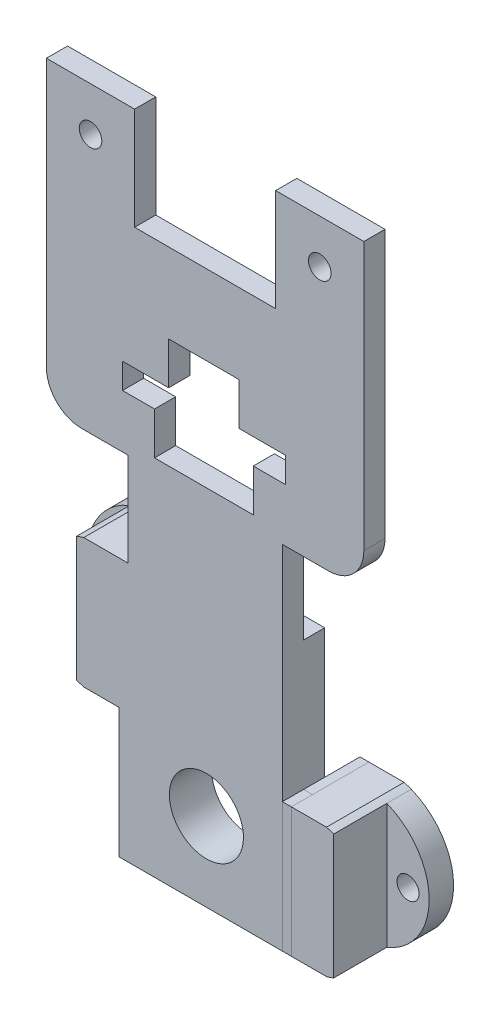
SolidWorks part; units mm, degrees
ref_plane "Front Plane" through (0, 0, 0) normal (0, 0, 1) x (1, 0, 0)
ref_plane "Top Plane" through (0, 0, 0) normal (0, 1, 0) x (1, 0, 0)
ref_plane "Right Plane" through (0, 0, 0) normal (1, 0, 0) x (0, 0, -1)
sketch "Sketch1" plane through (0, 0, 1119.4837) normal (0, 0, -1) x (-1, 0, 0)
  line L0 (-1148.8299, 505.6656) -> (-1128.8299, 505.6656) construction
  line L2 (-1161.3299, 505.6656) -> (-1161.3299, 518.1656)
  line L3 (-1161.3299, 518.1656) -> (-1148.8299, 518.1656)
  line L4 (-1148.8299, 505.6656) -> (-1148.8299, 518.1656)
  line L5 (-1161.3299, 505.6656) -> (-1148.8299, 518.1656) construction
  line L6 (-1161.3299, 518.1656) -> (-1148.8299, 505.6656) construction
  line L8 (-1128.8299, 505.6656) -> (-1128.8299, 518.1656)
  line L9 (-1128.8299, 518.1656) -> (-1116.3299, 518.1656)
  line L10 (-1116.3299, 505.6656) -> (-1116.3299, 518.1656)
  line L11 (-1128.8299, 505.6656) -> (-1116.3299, 518.1656) construction
  line L12 (-1128.8299, 518.1656) -> (-1116.3299, 505.6656) construction
  line L13 (-1128.8299, 505.6656) -> (-1148.8299, 505.6656) construction
  line L14 (-1148.8299, 518.1656) -> (-1128.8299, 518.1656) construction
  line L15 (-1138.8299, 518.1656) -> (-1138.8299, 426.1802) construction
  line L16 (-1148.8299, 505.6656) -> (-1128.8299, 505.6656) construction
  arc A0 (-1161.3299, 505.6656) -> (-1116.3299, 505.6656) centre (-1138.8299, 530.6919) ccw
  spline S0 degree 3 poles (-1148.8299, 505.6656) (-1142.1633, 505.6656) (-1135.4966, 505.6656) (-1128.8299, 505.6656) knots 0.277778 0.277778 0.277778 0.277778 0.722222 0.722222 0.722222 0.722222
  point P4 (-1155.0799, 511.9156)
  point P11 (-1122.5799, 511.9156)
  dimension "D1" = 33.6536
  dimension "D2" = 45
extrude "Boss-Extrude1" add sketch "Sketch1" along normal up to surface (17.8062 mm away)
sketch "Sketch4" plane through (0, 0, 1101.6775) normal (0, 0, -1) x (-1, 0, 0)
  line L0 (-1149.7799, 462.2666) -> (-1127.8799, 462.2666) construction
  line L1 (-1149.7799, 462.2666) -> (-1149.7799, 489.3928)
  line L2 (-1127.8799, 462.2666) -> (-1127.8799, 489.3928)
  line L4 (-1116.3299, 518.1656) -> (-1116.3299, 505.6656) construction
  line L5 (-1161.3299, 499.3928) -> (-1159.7799, 499.3928)
  line L6 (-1161.3299, 499.3928) -> (-1161.3299, 511.9156)
  line L7 (-1161.3299, 511.9156) -> (-1116.3299, 511.9156)
  line L8 (-1116.3299, 499.3928) -> (-1116.3299, 511.9156)
  line L9 (-1161.3299, 499.3928) -> (-1116.3299, 511.9156) construction
  line L10 (-1161.3299, 511.9156) -> (-1116.3299, 499.3928) construction
  line L11 (-1138.8299, 511.9156) -> (-1138.8299, 398.1731) construction
  line L12 (-1117.8799, 499.3928) -> (-1116.3299, 499.3928)
  line L13 (-1149.7799, 462.2666) -> (-1127.8799, 462.2666)
  arc A0 (-1127.5799, 461.9666) -> (-1127.8799, 462.2666) centre (-1127.8799, 461.9666) ccw construction
  arc A1 (-1127.5799, 461.9666) -> (-1127.8799, 462.2666) centre (-1127.8799, 461.9666) ccw construction
  arc A2 (-1117.8799, 499.3928) -> (-1127.8799, 489.3928) centre (-1117.8799, 489.3928) ccw
  arc A3 (-1149.7799, 489.3928) -> (-1159.7799, 499.3928) centre (-1159.7799, 489.3928) ccw
  point P11 (-1138.8299, 505.6542)
  point P22 (-1127.8799, 499.3928)
  dimension "D3" = 10
  dimension "D1" = 22.5
  dimension "D2" = 12.5228
extrude "Boss-Extrude2" add sketch "Sketch4" along normal blind 3
sketch "Sketch5" plane through (0, 462.2666, 0) normal (0, -1, 0) x (1, 0, 0)
  line L1 (1127.8799, 1098.6775) -> (1149.7799, 1098.6775)
  line L2 (1127.8799, 1098.6775) -> (1127.8799, 1101.6775)
  line L3 (1127.8799, 1101.6775) -> (1149.7799, 1101.6775)
  line L4 (1149.7799, 1098.6775) -> (1149.7799, 1101.6775)
  line L5 (1127.8799, 1098.6775) -> (1149.7799, 1101.6775) construction
  line L6 (1127.8799, 1101.6775) -> (1149.7799, 1098.6775) construction
  point P4 (1138.8299, 1100.1775)
extrude "Boss-Extrude3" add sketch "Sketch5" along normal up to surface (37 mm away)
sketch "Sketch7" plane through (0, 0, 1098.6775) normal (0, 0, -1) x (-1, 0, 0)
  circle A0 centre (-1139.0099, 436.4591) radius 5.25
  dimension "D1" = 10.5
extrude "Cut-Extrude1" cut sketch "Sketch7" against normal up to next
sketch "Sketch8" plane through (1127.8799, 0, 0) normal (-1, 0, 0) x (0, 0, 1)
  line L0 (1101.6775, 425.2666) -> (1101.6775, 489.3928) construction
  line L1 (1098.6775, 425.2666) -> (1101.6775, 425.2666)
  line L2 (1098.6775, 425.2666) -> (1098.6775, 461.9666)
  line L3 (1098.6775, 461.9666) -> (1101.6775, 461.9666)
  line L4 (1101.6775, 425.2666) -> (1101.6775, 461.9666)
  line L5 (1098.6775, 425.2666) -> (1101.6775, 461.9666) construction
  line L6 (1098.6775, 461.9666) -> (1101.6775, 425.2666) construction
  line L7 (1101.6775, 461.9666) -> (1101.9775, 461.9666) construction
  point P4 (1100.1775, 443.6166)
extrude "Boss-Extrude4" add sketch "Sketch8" along normal blind 1.27 separate body
sketch "Sketch9" plane through (1126.6099, 0, 0) normal (-1, 0, 0) x (0, 0, 1)
  line L0 (1101.6775, 425.2666) -> (1101.6775, 461.9666) construction
  line L1 (1098.6775, 461.9666) -> (1101.6775, 461.9666)
  line L2 (1098.6775, 461.9666) -> (1098.6775, 443.6166)
  line L3 (1098.6775, 443.6166) -> (1101.6775, 443.6166)
  line L4 (1101.6775, 461.9666) -> (1101.6775, 443.6166)
  line L5 (1098.6775, 461.9666) -> (1101.6775, 443.6166) construction
  line L6 (1098.6775, 443.6166) -> (1101.6775, 461.9666) construction
  point P4 (1100.1775, 452.7916)
extrude "Boss-Extrude5" add sketch "Sketch9" along normal blind 6
sketch "Sketch11" plane through (0, 0, 1101.6775) normal (0, 0, 1) x (1, 0, 0)
  line L1 (1120.6099, 461.9666) -> (1126.6099, 461.9666)
  line L2 (1120.6099, 461.9666) -> (1120.6099, 443.6166)
  line L3 (1120.6099, 443.6166) -> (1126.6099, 443.6166)
  line L4 (1126.6099, 461.9666) -> (1126.6099, 443.6166)
  line L5 (1120.6099, 461.9666) -> (1126.6099, 443.6166) construction
  line L6 (1120.6099, 443.6166) -> (1126.6099, 461.9666) construction
  point P4 (1123.6099, 452.7916)
extrude "Boss-Extrude6" add sketch "Sketch11" along normal blind 8
sketch "Sketch12" plane through (1120.6099, 0, 0) normal (-1, 0, 0) x (0, 0, 1)
  line L0 (1109.9156, 461.9666) -> (1101.9775, 461.9666) construction
  line L1 (1109.6775, 443.6166) -> (1103.6775, 443.6166)
  line L2 (1109.6775, 443.6166) -> (1109.6775, 461.9666)
  line L3 (1109.6775, 461.9666) -> (1103.6775, 461.9666)
  line L4 (1103.6775, 443.6166) -> (1103.6775, 461.9666)
  line L5 (1109.6775, 443.6166) -> (1103.6775, 461.9666) construction
  line L6 (1109.6775, 461.9666) -> (1103.6775, 443.6166) construction
  point P4 (1106.6775, 452.7916)
  dimension "D1" = 6
extrude "Boss-Extrude7" add sketch "Sketch12" along normal blind 6
sketch "Sketch14" plane through (0, 0, 1103.6775) normal (0, 0, -1) x (-1, 0, 0)
  line L0 (-1114.6099, 452.7916) -> (-1120.6099, 452.7916) construction
  line L1 (-1114.6099, 461.9666) -> (-1114.6099, 443.6166) construction
  line L2 (-1120.6099, 461.9666) -> (-1120.6099, 443.6166) construction
  circle A0 centre (-1117.6099, 452.7916) radius 1.5625
  dimension "D1" = 3.125
extrude "Cut-Extrude2" cut sketch "Sketch14" against normal through all
sketch "Sketch16" plane through (0, 0, 1098.6775) normal (0, 0, -1) x (-1, 0, 0)
  line L0 (-1126.6099, 443.6166) -> (-1126.6099, 461.9666) construction
  line L1 (-1120.6099, 461.9666) -> (-1127.8799, 461.9666) construction
  line L2 (-1126.6099, 461.9666) -> (-1126.6099, 463.8787)
  line L3 (-1126.6099, 463.8787) -> (-1111.6099, 463.8787)
  line L4 (-1111.6099, 463.8787) -> (-1111.6099, 441.8787)
  line L5 (-1111.6099, 441.8787) -> (-1126.6099, 441.8787)
  line L6 (-1126.6099, 443.6166) -> (-1126.6099, 425.2666) construction
  line L7 (-1126.6099, 441.8787) -> (-1126.6099, 443.6166)
  arc A0 (-1126.6099, 461.9666) -> (-1126.6099, 443.6166) centre (-1124.1175, 452.7916) cw
  dimension "D1" = 9.5075
  dimension "D2" = 15
  dimension "D3" = 22
  dimension "D4" = 1.9121
extrude "Cut-Extrude3" cut sketch "Sketch16" against normal through all
sketch "Sketch17" plane through (0, 0, 1098.6775) normal (0, 0, -1) x (-1, 0, 0)
  circle A0 centre (-1122.5799, 511.9156) radius 1.6
  circle A1 centre (-1155.0799, 511.9156) radius 1.6
  dimension "D1" = 3.2
extrude "Cut-Extrude4" cut sketch "Sketch17" against normal through all
sketch "Sketch18" plane through (0, 0, 1098.6775) normal (0, 0, -1) x (-1, 0, 0)
  circle A0 centre (-1155.0799, 511.9156) radius 2.5
  circle A1 centre (-1122.5799, 511.9156) radius 2.5
  dimension "D1" = 5
extrude "Cut-Extrude5" cut sketch "Sketch18" against normal up to surface (3 mm away) up to face at (1155.0799, 514.2656, 1101.6775)
fillet "Fillet8" radius 2 1 edges
ref_plane "Plane1" through (1138.8299, 0, 0) normal (1, 0, 0) x (0, 0, -1)
sketch "Sketch19" plane through (1149.7799, 0, 0) normal (1, 0, 0) x (0, 0, -1)
  line L0 (-1098.6775, 489.3928) -> (-1098.6775, 425.2666) construction
  line L1 (-1101.6775, 425.2666) -> (-1098.6775, 425.2666)
  line L2 (-1101.6775, 425.2666) -> (-1101.6775, 443.6166)
  line L3 (-1101.6775, 443.6166) -> (-1098.6775, 443.6166)
  line L4 (-1098.6775, 425.2666) -> (-1098.6775, 443.6166)
  line L5 (-1101.6775, 425.2666) -> (-1098.6775, 443.6166) construction
  line L6 (-1101.6775, 443.6166) -> (-1098.6775, 425.2666) construction
  point P4 (-1100.1775, 434.4416)
  dimension "D1" = 18.35
extrude "Boss-Extrude9" add sketch "Sketch19" along normal blind 1.27 separate body
sketch "Sketch20" plane through (0, 0, 1098.6775) normal (0, 0, -1) x (-1, 0, 0)
  line L0 (-1151.0499, 425.2666) -> (-1151.0499, 443.6166)
  line L1 (-1151.0499, 425.2666) -> (-1157.0499, 425.2666)
  line L2 (-1151.0499, 443.6166) -> (-1157.0499, 443.6166)
  line L3 (-1157.0499, 425.2666) -> (-1157.0499, 443.6166)
  dimension "D1" = 6
extrude "Boss-Extrude10" add sketch "Sketch20" against normal up to surface (11 mm away) separate body up to face at (1119.1724, 452.7916, 1109.6775)
sketch "Sketch21" plane through (1157.0499, 0, 0) normal (1, 0, 0) x (0, 0, -1)
  line L0 (-1109.6775, 425.2666) -> (-1098.6775, 425.2666) construction
  line L1 (-1109.6775, 443.6166) -> (-1103.6775, 443.6166)
  line L2 (-1109.6775, 443.6166) -> (-1109.6775, 425.2666)
  line L3 (-1109.6775, 425.2666) -> (-1103.6775, 425.2666)
  line L4 (-1103.6775, 443.6166) -> (-1103.6775, 425.2666)
  line L5 (-1109.6775, 443.6166) -> (-1103.6775, 425.2666) construction
  line L6 (-1109.6775, 425.2666) -> (-1103.6775, 443.6166) construction
  point P4 (-1106.6775, 434.4416)
  dimension "D1" = 6
extrude "Boss-Extrude12" add sketch "Sketch21" along normal blind 6 separate body
sketch "Sketch22" plane through (0, 0, 1103.6775) normal (0, 0, -1) x (-1, 0, 0)
  line L0 (-1160.0499, 443.6166) -> (-1160.0499, 425.2666) construction
  line L1 (-1163.0499, 443.6166) -> (-1157.0499, 443.6166) construction
  line L2 (-1163.0499, 425.2666) -> (-1157.0499, 425.2666) construction
  circle A0 centre (-1160.0499, 434.4416) radius 1.565
  dimension "D1" = 3.13
extrude "Cut-Extrude6" cut sketch "Sketch22" against normal through all
sketch "Sketch23" plane through (0, 0, 1103.6775) normal (0, 0, -1) x (-1, 0, 0)
  line L0 (-1151.0499, 425.2666) -> (-1151.0499, 419.4416)
  line L1 (-1151.0499, 419.4416) -> (-1166.0499, 419.4416)
  line L2 (-1166.0499, 419.4416) -> (-1166.0499, 449.4416)
  line L3 (-1166.0499, 449.4416) -> (-1151.0499, 449.4416)
  line L4 (-1151.0499, 449.4416) -> (-1151.0499, 443.6166)
  arc A1 (-1151.0499, 425.2666) -> (-1151.0499, 443.6166) centre (-1153.5424, 434.4416) cw
  dimension "D1" = 9.5075
  dimension "D2" = 15
  dimension "D3" = 30
extrude "Cut-Extrude7" cut sketch "Sketch23" against normal through all both and the other way through all
ref_plane "Plane4" through (0, 0, 1129.4837) normal (0, 0, 1) x (1, 0, 0)
mirror "Mirror4" about plane through (0, 0, 1129.4837) normal (0, 0, 1) of bodies 112 115 121 122
delete or keep bodies "Body-Delete/Keep 2" type delete bodies bodies 112 121 122 115
sketch "Sketch29" plane through (1161.3299, 0, 0) normal (1, 0, 0) x (0, 0, -1)
  line L1 (-1157.2899, 518.1656) -> (-1139.4837, 518.1656)
  line L2 (-1157.2899, 518.1656) -> (-1157.2899, 497.0383)
  line L3 (-1157.2899, 497.0383) -> (-1139.4837, 497.0383)
  line L4 (-1139.4837, 518.1656) -> (-1139.4837, 497.0383)
  line L5 (-1157.2899, 518.1656) -> (-1139.4837, 497.0383) construction
  line L6 (-1157.2899, 497.0383) -> (-1139.4837, 518.1656) construction
  point P4 (-1148.3868, 507.602)
extrude "Cut-Extrude11" cut sketch "Sketch29" against normal through all both and the other way through all
sketch "Sketch30" plane through (0, 0, 1157.2899) normal (0, 0, -1) x (-1, 0, 0)
  line L0 (-1126.6099, 425.2666) -> (-1149.7799, 425.2666) construction
  line L1 (-1161.3299, 511.9156) -> (-1116.3299, 511.9156)
  line L2 (-1161.3299, 511.9156) -> (-1161.3299, 475.2666)
  line L3 (-1161.3299, 475.2666) -> (-1116.3299, 475.2666)
  line L4 (-1116.3299, 511.9156) -> (-1116.3299, 475.2666)
  line L5 (-1161.3299, 511.9156) -> (-1116.3299, 475.2666) construction
  line L6 (-1161.3299, 475.2666) -> (-1116.3299, 511.9156) construction
  line L7 (-1149.7799, 489.3928) -> (-1149.7799, 425.2666) construction
  point P4 (-1138.8299, 493.5911)
  dimension "D1" = 50
  dimension "D2" = 10.95
extrude "Cut-Extrude12" cut sketch "Sketch30" against normal through all both and the other way through all
sketch "Sketch32" plane through (0, 0, 1160.2899) normal (0, 0, 1) x (1, 0, 0)
  line L5 (1116.3299, 518.1656) -> (1116.3299, 480.2117)
  line L6 (1161.3299, 518.1656) -> (1161.3299, 480.2117)
  line L7 (1121.3299, 475.2117) -> (1156.3299, 475.2117)
  line L8 (1116.3299, 518.1656) -> (1161.3299, 518.1656)
  arc A0 (1161.3299, 480.2117) -> (1156.3299, 475.2117) centre (1156.3299, 480.2117) cw
  arc A1 (1116.3299, 480.2117) -> (1121.3299, 475.2117) centre (1121.3299, 480.2117) ccw
  point P8 (1161.3299, 475.2117)
  dimension "D3" = 5
extrude "Boss-Extrude14" add sketch "Sketch32" against normal up to surface (3 mm away) up to face at (1133.5928, 452.6595, 1157.2899)
sketch "Sketch33" plane through (0, 0, 1160.2899) normal (0, 0, 1) x (1, 0, 0)
  line L0 (1145.6549, 476.7656) -> (1131.6549, 476.7656)
  line L1 (1134.6549, 491.3656) -> (1142.6549, 491.3656) construction
  line L2 (1134.6549, 491.3656) -> (1134.6549, 485.3656) construction
  line L3 (1134.6549, 485.3656) -> (1142.6549, 485.3656) construction
  line L4 (1142.6549, 491.3656) -> (1142.6549, 485.3656) construction
  line L5 (1134.6549, 491.3656) -> (1142.6549, 485.3656) construction
  line L6 (1134.6549, 485.3656) -> (1142.6549, 491.3656) construction
  line L7 (1132.6549, 477.7656) -> (1144.6549, 477.7656) construction
  line L8 (1132.6549, 477.7656) -> (1132.6549, 483.7656) construction
  line L9 (1132.6549, 483.7656) -> (1144.6549, 483.7656) construction
  line L10 (1144.6549, 477.7656) -> (1144.6549, 483.7656) construction
  line L11 (1132.6549, 477.7656) -> (1144.6549, 483.7656) construction
  line L12 (1132.6549, 483.7656) -> (1144.6549, 477.7656) construction
  line L13 (1129.6549, 485.3656) -> (1147.6549, 485.3656) construction
  line L14 (1129.6549, 485.3656) -> (1129.6549, 483.7656) construction
  line L15 (1129.6549, 483.7656) -> (1147.6549, 483.7656) construction
  line L16 (1147.6549, 485.3656) -> (1147.6549, 483.7656) construction
  line L17 (1129.6549, 485.3656) -> (1147.6549, 483.7656) construction
  line L18 (1129.6549, 483.7656) -> (1147.6549, 485.3656) construction
  line L19 (1147.6549, 484.5656) -> (1150.1549, 484.5656) construction
  line L20 (1131.6549, 476.7656) -> (1131.6549, 482.7656)
  line L21 (1138.6549, 491.3656) -> (1138.6549, 492.3656) construction
  line L22 (1138.6549, 477.7656) -> (1138.6549, 476.7656) construction
  line L23 (1132.6549, 480.7656) -> (1131.6549, 480.7656) construction
  line L24 (1131.6549, 482.7656) -> (1127.1149, 482.7656)
  line L25 (1127.1149, 482.7656) -> (1127.1149, 486.3656)
  line L26 (1127.1149, 486.3656) -> (1133.6549, 486.3656)
  line L27 (1133.6549, 486.3656) -> (1133.6549, 492.3656)
  line L28 (1133.6549, 492.3656) -> (1143.6549, 492.3656)
  line L29 (1145.6549, 476.7656) -> (1145.6549, 482.7656)
  line L30 (1145.6549, 482.7656) -> (1150.1949, 482.7656)
  line L31 (1150.1949, 482.7656) -> (1150.1949, 486.3656)
  line L32 (1150.1949, 486.3656) -> (1143.6549, 486.3656)
  line L33 (1143.6549, 486.3656) -> (1143.6549, 492.3656)
  point P4 (1138.6549, 488.3656)
  point P9 (1138.6549, 480.7656)
  point P14 (1138.6549, 484.5656)
  point P22 (1127.1549, 484.5656)
  dimension "D1" = 1
  dimension "D2" = 1
  dimension "D3" = 1
  dimension "D4" = 1
  dimension "D5" = 1
  dimension "D6" = 1
  dimension "D7" = 2.54
  dimension "D8" = 4
  dimension "D9" = 6
  dimension "D10" = 4.54
  dimension "D11" = 3.6
  dimension "D12" = 6.54
  dimension "D13" = 6
  dimension "D14" = 5
  dimension "D15" = 4
  dimension "D16" = 3.8
extrude "Cut-Extrude13" cut sketch "Sketch33" against normal through all both and the other way through all
sketch "Sketch35" plane through (0, 0, 1160.2899) normal (0, 0, 1) x (1, 0, 0)
  line L1 (1128.8299, 518.1656) -> (1148.8299, 518.1656)
  line L2 (1128.8299, 518.1656) -> (1128.8299, 503.6656)
  line L3 (1128.8299, 503.6656) -> (1148.8299, 503.6656)
  line L4 (1148.8299, 518.1656) -> (1148.8299, 503.6656)
  line L5 (1128.8299, 518.1656) -> (1148.8299, 503.6656) construction
  line L6 (1128.8299, 503.6656) -> (1148.8299, 518.1656) construction
  point P4 (1138.8299, 510.9156)
  dimension "D1" = 14.5
  dimension "D2" = 20
extrude "Cut-Extrude15" cut sketch "Sketch35" against normal through all both and the other way through all
sketch "Sketch36" plane through (0, 0, 1160.2899) normal (0, 0, 1) x (1, 0, 0)
  circle A0 centre (1122.5799, 511.9156) radius 1.6
  circle A1 centre (1155.0799, 511.9156) radius 1.6
  dimension "D1" = 3.2
  dimension "D2" = 3.2
extrude "Cut-Extrude16" cut sketch "Sketch36" against normal through all both and the other way through all
sketch "Sketch37" plane through (0, 0, 1157.2899) normal (0, 0, -1) x (-1, 0, 0)
  line L1 (-1149.7799, 425.2666) -> (-1127.8799, 425.2666)
  line L2 (-1149.7799, 425.2666) -> (-1149.7799, 461.9666)
  line L3 (-1149.7799, 461.9666) -> (-1127.8799, 461.9666)
  line L4 (-1127.8799, 425.2666) -> (-1127.8799, 461.9666)
  line L5 (-1149.7799, 425.2666) -> (-1127.8799, 461.9666) construction
  line L6 (-1149.7799, 461.9666) -> (-1127.8799, 425.2666) construction
  point P4 (-1138.8299, 443.6166)
extrude "Boss-Extrude16" add sketch "Sketch37" along normal blind 3 separate body
sketch "Sketch38" plane through (0, 0, 1157.2899) normal (0, 0, 1) x (1, 0, 0)
  circle A0 centre (1139.0099, 436.4591) radius 5.25
extrude "Cut-Extrude17" cut sketch "Sketch38" against normal through all both and the other way through all
sketch "Sketch39" plane through (0, 425.2666, 0) normal (0, -1, 0) x (1, 0, 0)
  line L1 (1127.8799, 1157.2899) -> (1149.7799, 1157.2899)
  line L2 (1127.8799, 1157.2899) -> (1127.8799, 1149.2899)
  line L3 (1127.8799, 1149.2899) -> (1149.7799, 1149.2899)
  line L4 (1149.7799, 1157.2899) -> (1149.7799, 1149.2899)
  line L5 (1127.8799, 1157.2899) -> (1149.7799, 1149.2899) construction
  line L6 (1127.8799, 1149.2899) -> (1149.7799, 1157.2899) construction
  point P4 (1138.8299, 1153.2899)
  dimension "D1" = 8
  dimension "D2" = 21.9
extrude "Boss-Extrude17" add sketch "Sketch39" along normal blind 3
sketch "Sketch40" plane through (1151.0499, 0, 0) normal (-1, 0, 0) x (0, 0, 1)
  line L1 (1149.2899, 443.6166) -> (1157.2899, 443.6166)
  line L2 (1149.2899, 443.6166) -> (1149.2899, 425.2666)
  line L3 (1149.2899, 425.2666) -> (1157.2899, 425.2666)
  line L4 (1157.2899, 443.6166) -> (1157.2899, 425.2666)
  line L5 (1149.2899, 443.6166) -> (1157.2899, 425.2666) construction
  line L6 (1149.2899, 425.2666) -> (1157.2899, 443.6166) construction
  point P4 (1153.2899, 434.4416)
extrude "Boss-Extrude19" add sketch "Sketch40" along normal up to surface (1.27 mm away) separate body up to face at (1149.7799, 441.9956, 1155.6899)
sketch "Sketch41" plane through (1126.6099, 0, 0) normal (1, 0, 0) x (0, 0, -1)
  line L1 (-1149.2899, 461.9666) -> (-1157.2899, 461.9666)
  line L2 (-1149.2899, 461.9666) -> (-1149.2899, 443.6166)
  line L3 (-1149.2899, 443.6166) -> (-1157.2899, 443.6166)
  line L4 (-1157.2899, 461.9666) -> (-1157.2899, 443.6166)
  line L5 (-1149.2899, 461.9666) -> (-1157.2899, 443.6166) construction
  line L6 (-1149.2899, 443.6166) -> (-1157.2899, 461.9666) construction
  point P4 (-1153.2899, 452.7916)
extrude "Boss-Extrude20" add sketch "Sketch41" along normal up to surface (1.27 mm away) separate body up to face at (1127.8799, 434.8952, 1154.1471)
sketch "Sketch42" plane through (1120.6099, 0, 0) normal (-1, 0, 0) x (0, 0, 1)
  line L0 (1149.2899, 443.6166) -> (1160.2899, 443.6166) construction
  line L1 (1160.2899, 461.9666) -> (1152.7499, 461.9666)
  line L2 (1160.2899, 461.9666) -> (1160.2899, 443.6166)
  line L3 (1160.2899, 443.6166) -> (1152.7499, 443.6166)
  line L4 (1152.7499, 461.9666) -> (1152.7499, 443.6166)
  line L5 (1160.2899, 461.9666) -> (1152.7499, 443.6166) construction
  line L6 (1160.2899, 443.6166) -> (1152.7499, 461.9666) construction
  line L7 (1152.7499, 452.7916) -> (1155.2899, 452.7916) construction
  line L8 (1155.2899, 461.6285) -> (1155.2899, 443.9547) construction
  point P4 (1156.5199, 452.7916)
  dimension "D1" = 2.54
extrude "Cut-Extrude18" cut sketch "Sketch42" along normal through all
sketch "Sketch43" plane through (1157.0499, 0, 0) normal (1, 0, 0) x (0, 0, -1)
  line L0 (-1149.2899, 425.2666) -> (-1157.2899, 425.2666) construction
  line L1 (-1160.2899, 443.6166) -> (-1152.7499, 443.6166)
  line L2 (-1160.2899, 443.6166) -> (-1160.2899, 425.2666)
  line L3 (-1160.2899, 425.2666) -> (-1152.7499, 425.2666)
  line L4 (-1152.7499, 443.6166) -> (-1152.7499, 425.2666)
  line L5 (-1160.2899, 443.6166) -> (-1152.7499, 425.2666) construction
  line L6 (-1160.2899, 425.2666) -> (-1152.7499, 443.6166) construction
  line L7 (-1155.2899, 434.4416) -> (-1152.7499, 434.4416) construction
  line L8 (-1155.2899, 443.2785) -> (-1155.2899, 425.6047) construction
  point P4 (-1156.5199, 434.4416)
  dimension "D1" = 2.54
extrude "Cut-Extrude19" cut sketch "Sketch43" along normal through all
